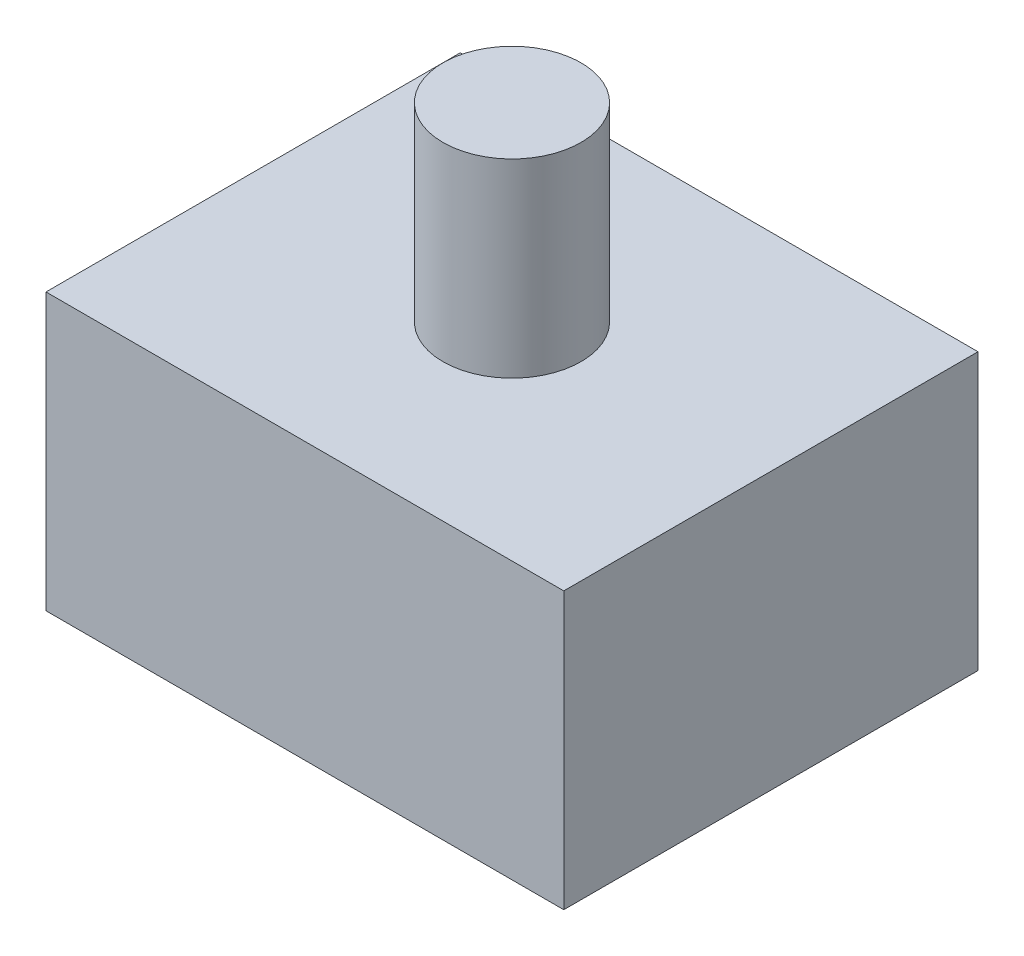
SolidWorks part; units mm, degrees
ref_plane "前视基准面" through (0, 0, 0) normal (0, 0, 1) x (1, 0, 0)
ref_plane "上视基准面" through (0, 0, 0) normal (0, 1, 0) x (1, 0, 0)
ref_plane "右视基准面" through (0, 0, 0) normal (1, 0, 0) x (0, 0, -1)
other "Configuration Table"
sketch "草图1" plane through (0, 0, 0) normal (0, 1, 0) x (1, 0, 0)
  line L1 (-15, 12) -> (15, 12)
  line L2 (-15, 12) -> (-15, -12)
  line L3 (-15, -12) -> (15, -12)
  line L4 (15, 12) -> (15, -12)
  line L5 (-15, 12) -> (15, -12) construction
  line L6 (-15, -12) -> (15, 12) construction
  point P0 (0, 0)
  dimension "D1" = 30
  dimension "D2" = 24
extrude "凸台-拉伸1" add sketch "草图1" along normal blind 16
sketch "草图2" plane through (0, 16, 0) normal (0, 1, 0) x (1, 0, 0)
  circle A0 centre (0, 0) radius 4
  dimension "D1" = 8
extrude "凸台-拉伸2" add sketch "草图2" along normal blind 11
